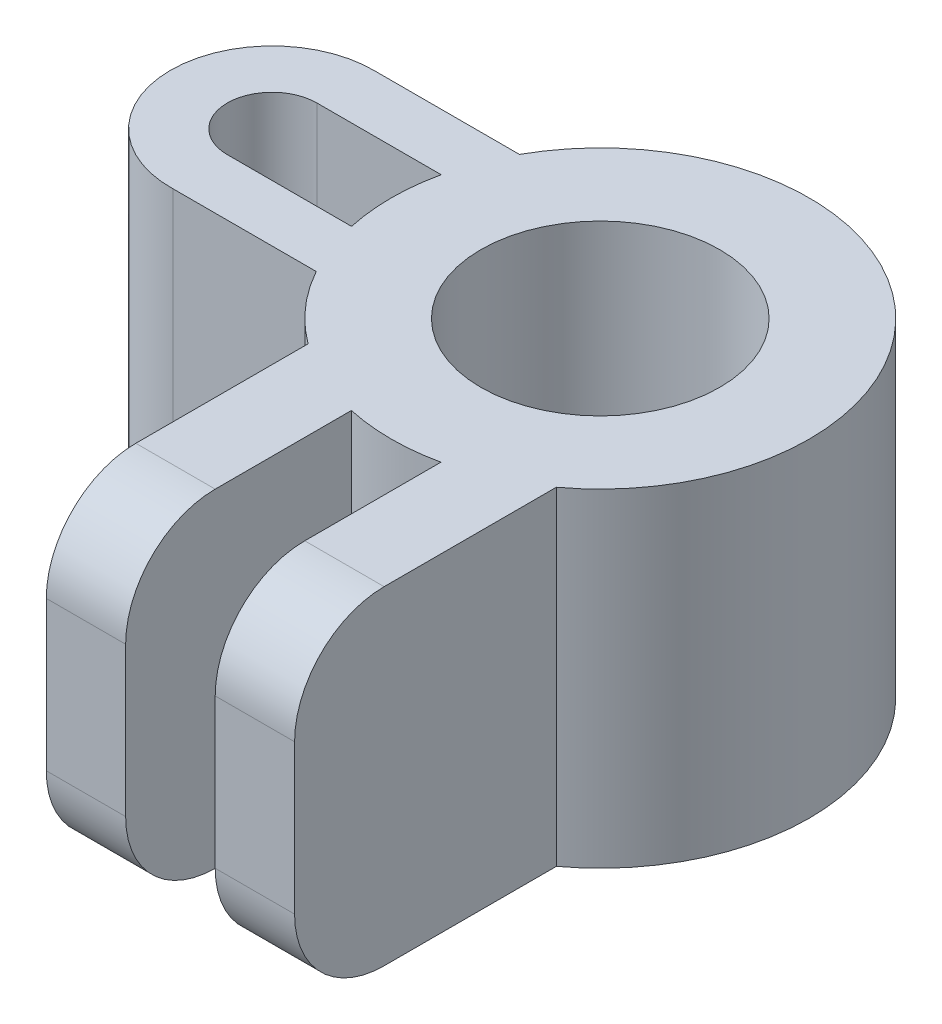
SolidWorks part; units mm, degrees
ref_plane "Front Plane" through (0, 0, 0) normal (0, 0, 1) x (1, 0, 0)
ref_plane "Top Plane" through (0, 0, 0) normal (0, 1, 0) x (1, 0, 0)
ref_plane "Right Plane" through (0, 0, 0) normal (1, 0, 0) x (0, 0, -1)
sketch "Sketch2" plane through (0, 0, 0) normal (0, 1, 0) x (1, 0, 0)
  line L0 (0, 0) -> (0, -99.4573) construction
  line L1 (-20.7954, -72) -> (-20.7954, -28.1523)
  line L2 (-7.5, -72) -> (-20.7954, -72)
  line L3 (7.5, -34.187) -> (7.5, -72)
  line L4 (7.5, -72) -> (20.7954, -72)
  line L5 (20.7954, -72) -> (20.7954, -28.1523)
  line L6 (-30.6112, -16.9692) -> (-54.6112, -16.9692)
  line L7 (-30.577, 17.0308) -> (-54.577, 17.0308)
  line L8 (-34.1801, 7.5312) -> (-54.9863, 7.5312)
  line L9 (-55, -7.4688) -> (-34.1938, -7.4688)
  line L10 (-7.5, -34.187) -> (-7.5, -72)
  circle A0 centre (0, 0) radius 20
  circle A1 centre (0, 0) radius 35
  arc A2 (-54.577, 17.0308) -> (-54.6112, -16.9692) centre (-55, 0.0312) ccw
  arc A3 (-54.9863, 7.5312) -> (-55, -7.4688) centre (-55, 0.0312) ccw
  point P13 (-42.577, 17.0308)
  point P24 (-210.5869, -52.1162)
  dimension "D1" = 70
  dimension "D2" = 40
  dimension "D5" = 15
  dimension "D9" = 55
  dimension "D4" = 13.2954
  dimension "D6" = 34
  dimension "D8" = 15
extrude "Boss-Extrude3" add sketch "Sketch2" along normal blind 55
fillet "Fillet1" radius 15 4 edges at (14.1477, 0, 72) (14.1477, 55, 72) (-14.1477, 0, 72) (-14.1477, 55, 72)
